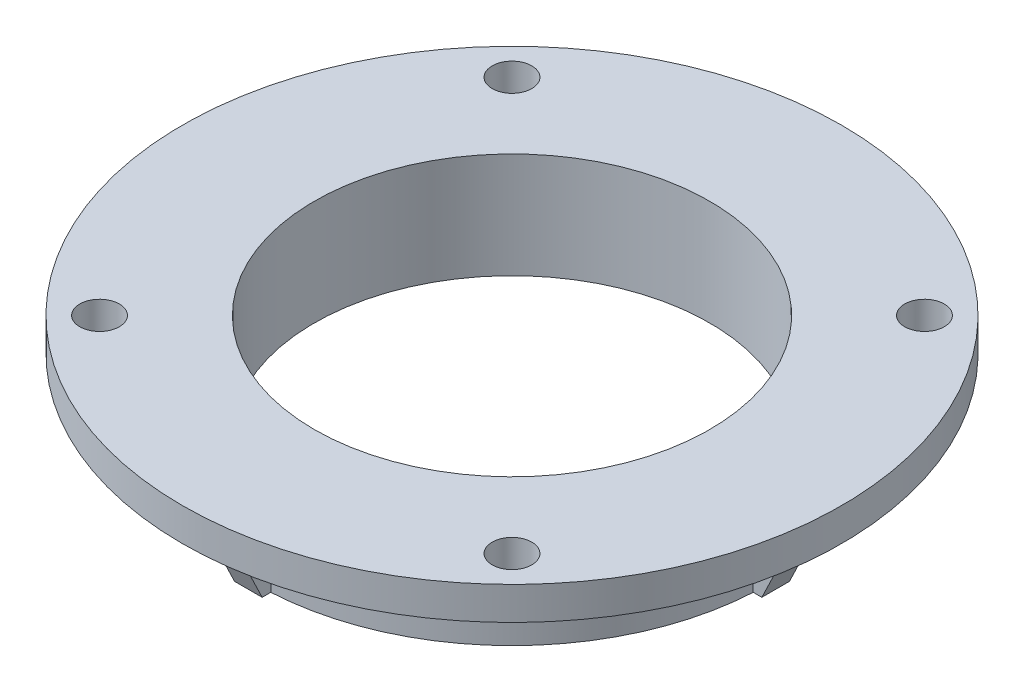
SolidWorks part; units mm, degrees
ref_plane "Ön Düzlem" through (0, 0, 0) normal (0, 0, 1) x (1, 0, 0)
ref_plane "Üst Düzlem" through (0, 0, 0) normal (0, 1, 0) x (1, 0, 0)
ref_plane "Sağ Düzlem" through (0, 0, 0) normal (1, 0, 0) x (0, 0, -1)
sketch "Çizim1" plane through (0, 0, 0) normal (0, 1, 0) x (1, 0, 0)
  circle A0 centre (0, 0) radius 60
  circle A1 centre (0, 0) radius 77.5
  circle A2 centre (0, 70) radius 4.19
  circle A3 centre (70, 0) radius 4.19
  circle A4 centre (0, -70) radius 4.19
  circle A5 centre (-70, 0) radius 4.19
  point P6 (-68.9018, -6.085)
  point P7 (70, 4.5691)
  dimension "D1" = 155
  dimension "D2" = 120
  dimension "D3" = 8.38
  dimension "D4" = 70
  dimension "D6" = 70
  dimension "D5" = 4
extrude "Yükseklik-Ekstrüzyon1" add sketch "Çizim1" along normal blind 10
sketch "Çizim2" plane through (0, 10, 0) normal (0, 1, 0) x (1, 0, 0)
  circle A0 centre (0, 0) radius 77.5
  circle A1 centre (0, 0) radius 60
extrude "Yükseklik-Ekstrüzyon2" add sketch "Çizim2" along normal blind 22
sketch "Çizim3" plane through (0, 32, 0) normal (0, 1, 0) x (1, 0, 0)
  circle A0 centre (0, 0) radius 100
  circle A1 centre (0, 0) radius 60
  dimension "D1" = 200
  dimension "D2" = 120
extrude "Yükseklik-Ekstrüzyon3" add sketch "Çizim3" against normal blind 10
sketch "Çizim4" plane through (0, 0, 0) normal (0, 0, 1) x (1, 0, 0)
  line L3 (0, -15.3558) -> (0, 40.2794) construction
  point P12 (0, 0)
  point P15 (-77.5, 2.0711)
  point P16 (77.5, 11.1098)
ref_plane "Düzlem1" through (0, 0, 80) normal (0, 0, 1) x (1, 0, 0)
sketch "Çizim5" plane through (0, 0, 80) normal (0, 0, 1) x (1, 0, 0)
  line L0 (0, -15.3558) -> (0, 40.2794) construction
  line L1 (4.19, 0) -> (-4.19, 0)
  line L2 (4.19, 0) -> (4.19, 22)
  line L3 (4.19, 22) -> (-4.19, 22)
  line L4 (-4.19, 0) -> (-4.19, 22)
  line L5 (0, 22) -> (0, 0) construction
  line L6 (4.19, 11) -> (-4.19, 11) construction
  line L7 (-100, 22) -> (100, 22) construction
  point P0 (0, 11)
  point P8 (-4.19, 0)
extrude "Yükseklik-Ekstrüzyon4" add sketch "Çizim5" against normal up to next
pattern_circular "Dairesel Kaplama1" count 4 over 360 about axis through (0, 0, 0) along (0, 1, 0) of "Yükseklik-Ekstrüzyon4"
sketch "Çizim6" plane through (0, 0, 0) normal (1, 0, 0) x (0, 0, -1)
  line L0 (-80, 0) -> (-90.6019, 22)
  line L1 (-100, 22) -> (100, 22) construction
  point P5 (-90.6019, 22)
  point P6 (0, 0)
extrude "Ekstrüzyon-İnce4" add sketch "Çizim6" along normal mid plane 8.38 thin
pattern_circular "Dairesel Kaplama2" count 4 over 360 about axis through (0, 0, 0) along (0, 1, 0) of "Ekstrüzyon-İnce4"
sketch "Çizim7" plane through (0, 0, 0) normal (0, -1, 0) x (1, 0, 0)
  circle A0 centre (70, 0) radius 4.19
  circle A1 centre (0, -70) radius 4.19
  circle A2 centre (-70, 0) radius 4.19
  circle A3 centre (0, 70) radius 4.19
  dimension "D1" = 8.38
  dimension "D2" = 4
extrude "Kes-Ekstrüzyon1" cut sketch "Çizim7" against normal blind 10
sketch "Çizim8" plane through (0, 22, 0) normal (0, -1, 0) x (1, 0, 0)
  line L0 (0, 149.0651) -> (0, -153.325) construction
  line L1 (152.6934, 0) -> (-151.7656, 0) construction
  line L2 (-27.9772, 27.9772) -> (99.7768, -99.7768) construction
  line L3 (-100.5538, -100.5538) -> (100.5538, 100.5538) construction
  circle A0 centre (62.579, -62.579) radius 6
  circle A1 centre (-62.579, -62.579) radius 6
  circle A2 centre (-62.579, 62.579) radius 6
  circle A3 centre (62.579, 62.579) radius 6
  point P9 (62.579, 62.579)
  point P12 (62.579, 63.0922)
  dimension "D3" = 12
  dimension "D1" = 45
  dimension "D2" = 45
  dimension "D4" = 88.5
  dimension "D6" = 88.5
  dimension "D5" = 4
extrude "Kes-Ekstrüzyon2" cut sketch "Çizim8" against normal through all
